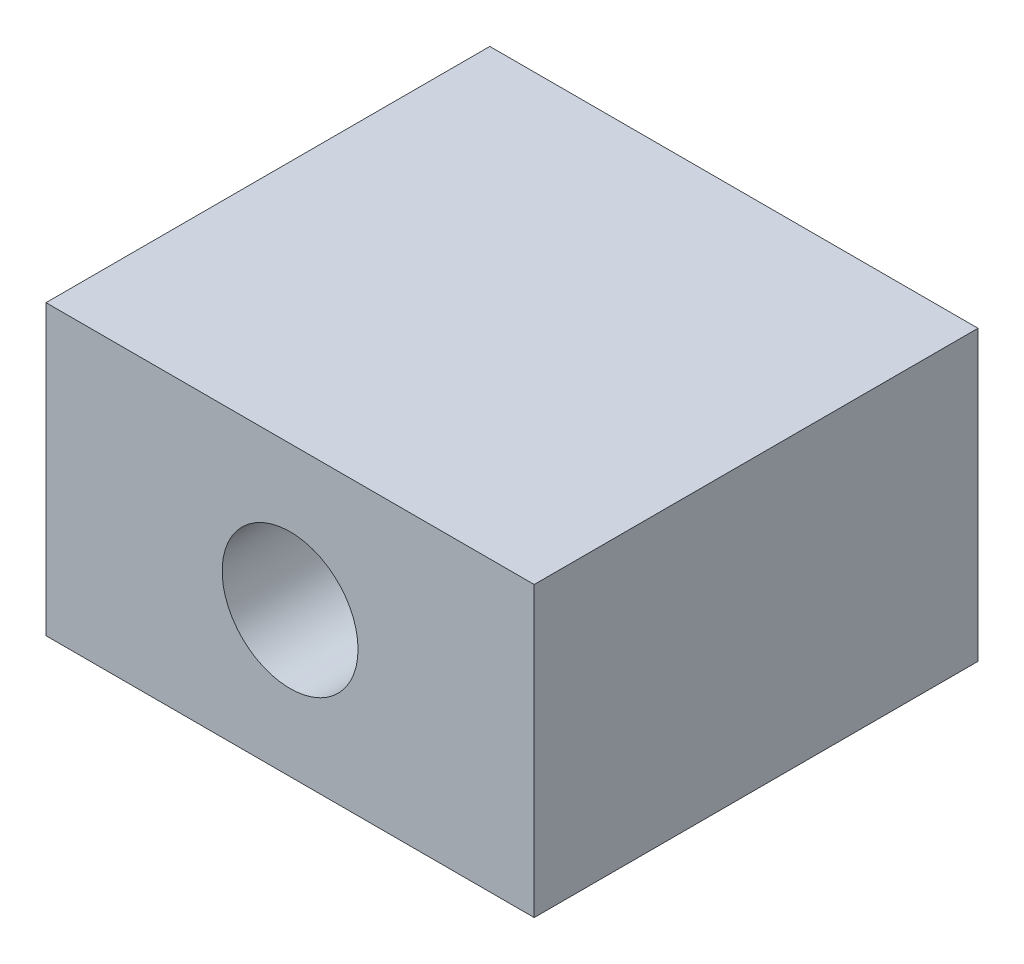
SolidWorks part; units mm, degrees
ref_plane "Front Plane" through (0, 0, 0) normal (0, 0, 1) x (1, 0, 0)
ref_plane "Top Plane" through (0, 0, 0) normal (0, 1, 0) x (1, 0, 0)
ref_plane "Right Plane" through (0, 0, 0) normal (1, 0, 0) x (0, 0, -1)
sketch "Sketch1" plane through (0, 0, 0) normal (0, 0, 1) x (1, 0, 0)
  line L1 (-139.7, -82.55) -> (139.7, -82.55)
  line L2 (-139.7, -82.55) -> (-139.7, 82.55)
  line L3 (-139.7, 82.55) -> (139.7, 82.55)
  line L4 (139.7, -82.55) -> (139.7, 82.55)
  line L5 (-139.7, -82.55) -> (139.7, 82.55) construction
  line L6 (-139.7, 82.55) -> (139.7, -82.55) construction
  point P0 (0, 0)
extrude "Boss-Extrude1" add sketch "Sketch1" along normal blind 254
sketch "Sketch2" plane through (0, 0, 0) normal (0, 0, 1) x (1, 0, 0)
  circle A0 centre (0, 0) radius 38.8874
extrude "Cut-Extrude1" cut sketch "Sketch2" along normal through all
